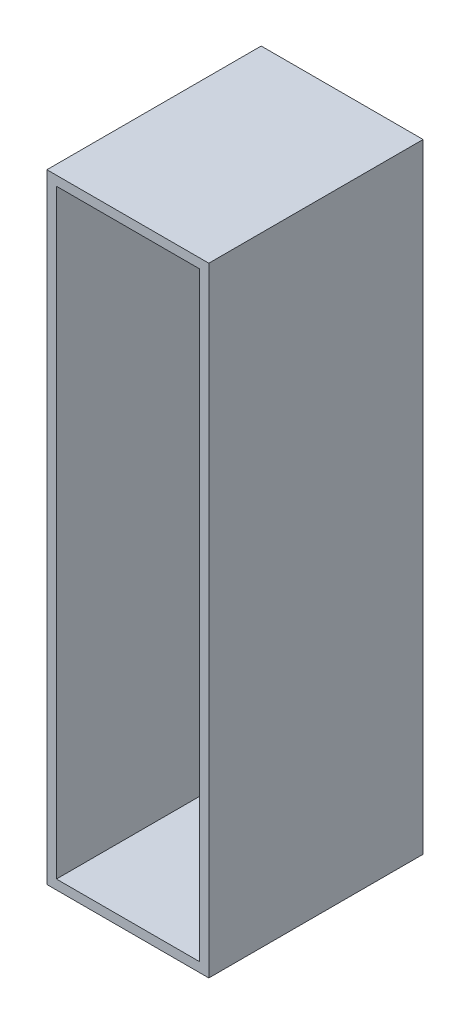
SolidWorks part; units mm, degrees
ref_plane "Front Plane" through (0, 0, 0) normal (0, 0, 1) x (1, 0, 0)
ref_plane "Top Plane" through (0, 0, 0) normal (0, 1, 0) x (1, 0, 0)
ref_plane "Right Plane" through (0, 0, 0) normal (1, 0, 0) x (0, 0, -1)
sketch "Sketch1" plane through (0, 0, 0) normal (0, 0, 1) x (1, 0, 0)
  line L1 (0, 0) -> (34, 0)
  line L2 (0, 0) -> (0, 130)
  line L3 (0, 130) -> (34, 130)
  line L4 (34, 0) -> (34, 130)
  line L5 (2, 2) -> (32, 2)
  line L6 (2, 2) -> (2, 128)
  line L7 (2, 128) -> (32, 128)
  line L8 (32, 2) -> (32, 128)
  dimension "D1" = 2
  dimension "D2" = 32
  dimension "D3" = 34
  dimension "D4" = 2
  dimension "D5" = 128
  dimension "D6" = 130
extrude "Profile" add sketch "Sketch1" along normal blind 45
sketch "Sketch2" plane through (0, 0, 0) normal (0, 0, 1) x (1, 0, 0)
  line L1 (2, 2) -> (32, 2)
  line L2 (2, 2) -> (2, 128)
  line L3 (2, 128) -> (32, 128)
  line L4 (32, 2) -> (32, 128)
extrude "Back" add sketch "Sketch2" along normal blind 2
equation "\"Profile_Depth\" = 45mm"
equation "\"D1@Profile\" = \"Profile_Depth\""
equation "\"Profile_Sketch_1\" = 2mm"
equation "\"D1@Sketch1\" = \"Profile_Sketch_1\""
equation "\"Profile_Sketch_2\" = 32mm"
equation "\"D2@Sketch1\" = \"Profile_Sketch_2\""
equation "\"Profile_Sketch_3\" = 34mm"
equation "\"D3@Sketch1\" = \"Profile_Sketch_3\""
equation "\"Profile_Sketch_4\" = 2mm"
equation "\"D4@Sketch1\" = \"Profile_Sketch_4\""
equation "\"Profile_Sketch_5\" = 128mm"
equation "\"D5@Sketch1\" = \"Profile_Sketch_5\""
equation "\"Profile_Sketch_6\" = 130mm"
equation "\"D6@Sketch1\" = \"Profile_Sketch_6\""
equation "\"Back_Depth\" = 2mm"
equation "\"D1@Back\" = \"Back_Depth\""
equation "\"EnvelopeWidth\" = 34mm"
equation "\"EnvelopeHeight\" = 130mm"
